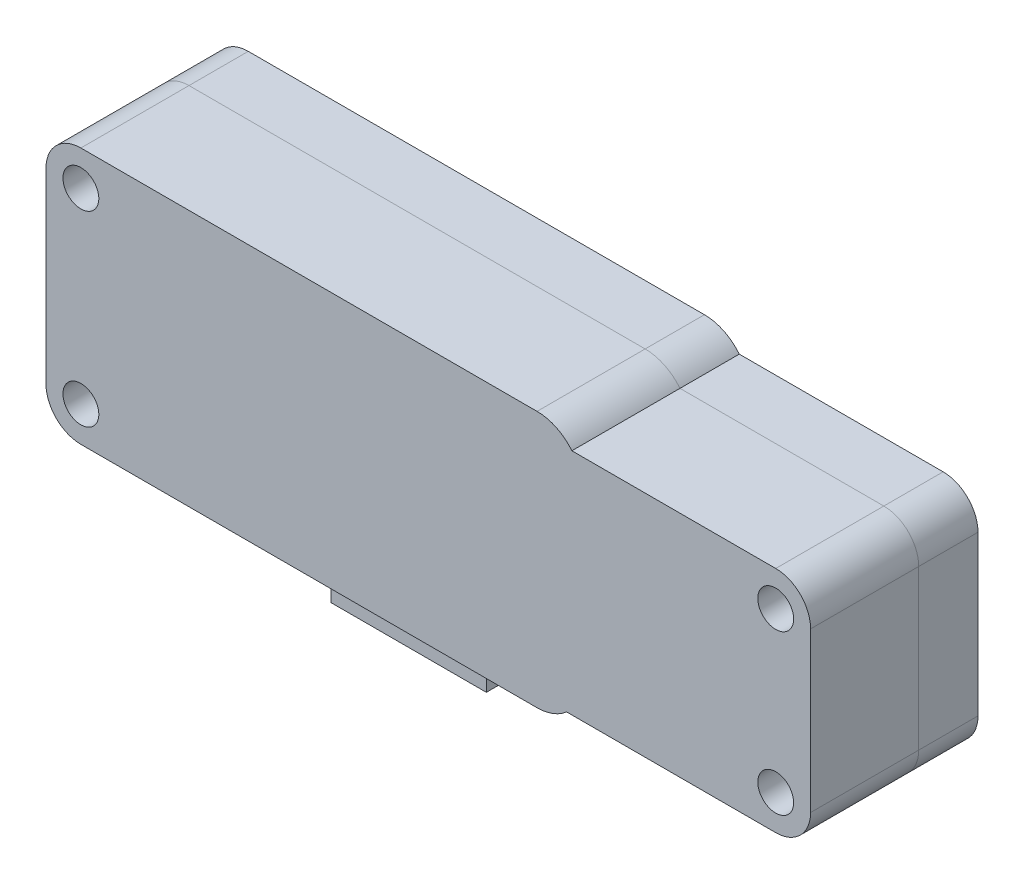
SolidWorks part; units mm, degrees
ref_plane "Front Plane" through (0, 0, 0) normal (0, 0, 1) x (1, 0, 0)
ref_plane "Top Plane" through (0, 0, 0) normal (0, 1, 0) x (1, 0, 0)
ref_plane "Right Plane" through (0, 0, 0) normal (1, 0, 0) x (0, 0, -1)
sketch "Sketch1" plane through (0, 0, 2.064) normal (0, 0, 1) x (1, 0, 0)
  line L8 (-21.844, 7.62) -> (-21.844, -7.62)
  line L9 (17.78, 11.684) -> (-17.78, 11.684)
  line L10 (21.844, -7.62) -> (21.844, 7.62)
  line L11 (-17.78, -11.684) -> (17.78, -11.684)
  line L12 (-21.844, 7.62) -> (-21.844, -7.62)
  line L13 (17.78, 11.684) -> (-17.78, 11.684)
  line L14 (21.844, -7.62) -> (21.844, 7.62)
  line L15 (-17.78, -11.684) -> (17.78, -11.684)
  arc A8 (-17.78, 11.684) -> (-21.844, 7.62) centre (-17.78, 7.62) ccw
  arc A9 (21.844, 7.62) -> (17.78, 11.684) centre (17.78, 7.62) ccw
  arc A10 (17.78, -11.684) -> (21.844, -7.62) centre (17.78, -7.62) ccw
  arc A11 (-21.844, -7.62) -> (-17.78, -11.684) centre (-17.78, -7.62) ccw
  arc A12 (-17.78, 11.684) -> (-21.844, 7.62) centre (-17.78, 7.62) ccw
  arc A13 (21.844, 7.62) -> (17.78, 11.684) centre (17.78, 7.62) ccw
  arc A14 (17.78, -11.684) -> (21.844, -7.62) centre (17.78, -7.62) ccw
  arc A15 (-21.844, -7.62) -> (-17.78, -11.684) centre (-17.78, -7.62) ccw
  dimension "D1" = 1.524
extrude "Boss-Extrude1" add sketch "Sketch1" against normal blind 12.7 from offset 0.508
ref_plane "Plane2" through (0, 0, -4) normal (0, 0, -1) x (-1, 0, 0)
sketch "Sketch2" plane through (0, 0, -4) normal (0, 0, -1) x (-1, 0, 0)
  line L3 (4.276, -16.0786) -> (4.276, -8.1284)
  line L4 (3.006, -14.8086) -> (-8.594, -14.8086) construction
  line L5 (3.006, -14.8086) -> (3.006, -9.3984) construction
  line L6 (3.006, -9.3984) -> (-8.594, -9.3984) construction
  line L7 (-8.594, -14.8086) -> (-8.594, -9.3984) construction
  line L8 (4.276, -8.1284) -> (-9.864, -8.1284)
  line L9 (-9.864, -16.0786) -> (-9.864, -8.1284)
  line L10 (4.276, -16.0786) -> (-9.864, -16.0786)
  line L12 (3.006, -14.8086) -> (3.006, -9.3984) construction
  line L13 (-8.594, -14.8086) -> (-3.048, -14.8086) construction
  dimension "D1" = 1.27
extrude "Boss-Extrude2" add sketch "Sketch2" along normal offset from surface 1.27 and the other way offset from surface (3.27 mm away) 1.27
sketch "Sketch3" plane through (0, 0, -10.128) normal (0, 0, -1) x (-1, 0, 0)
  line L1 (-2.794, 8.8916) -> (-36.334, 8.8916) construction
  line L2 (-2.794, 8.8916) -> (-2.794, -9.3984) construction
  line L3 (-2.794, -9.3984) -> (-36.334, -9.3984) construction
  line L4 (-36.334, 8.8916) -> (-36.334, -9.3984) construction
  line L5 (-36.334, 8.8916) -> (-36.334, -9.3984) construction
  line L6 (-36.334, -9.3984) -> (-2.794, -9.3984) construction
  line L7 (-1.524, 10.1616) -> (-37.604, 10.1616)
  line L8 (-37.604, 10.1616) -> (-37.604, -10.6684)
  line L9 (-1.524, -10.6684) -> (-37.604, -10.6684)
  line L10 (-1.524, 10.1616) -> (-1.524, -10.6684)
  dimension "D1" = 1.27
extrude "Boss-Extrude3" add sketch "Sketch3" along normal blind 2.54 and the other way up to surface contours L9 L8 L7 L10 other way up to face at (0, 0, 2.572)
sketch "Sketch7" plane through (0, -16.0786, 0) normal (0, -1, 0) x (1, 0, 0)
  line L0 (-0.218, -5.762) -> (-0.218, -2.238)
  line L1 (0.544, -5) -> (5.044, -5) construction
  line L2 (0.544, -5) -> (0.544, -3) construction
  line L3 (0.544, -3) -> (5.044, -3) construction
  line L4 (5.044, -5) -> (5.044, -3) construction
  line L5 (-0.218, -2.238) -> (5.806, -2.238)
  line L6 (5.806, -5.762) -> (5.806, -2.238)
  line L7 (-0.218, -5.762) -> (5.806, -5.762)
  dimension "D1" = 0.762
extrude "Cut-Extrude1" cut sketch "Sketch7" against normal blind 2.54
sketch "Sketch11" plane through (0, 0, -10.128) normal (0, 0, -1) x (-1, 0, 0)
  line L4 (17.78, 11.684) -> (23.749, 11.684)
  line L5 (26.924, 7.62) -> (26.924, -7.62)
  line L6 (26.924, 8.509) -> (26.924, -8.509)
  line L7 (17.78, -11.684) -> (23.749, -11.684)
  line L8 (-20.9512, 10.1616) -> (-1.524, 10.1616)
  line L9 (-20.9512, 10.1616) -> (-1.524, 10.1616)
  line L12 (-1.524, 10.1616) -> (-1.524, -10.6684)
  line L13 (-1.524, 10.1616) -> (-1.524, -10.6684)
  line L14 (-1.524, -10.6684) -> (-20.4677, -10.6684)
  line L15 (-1.524, -10.6684) -> (-20.4677, -10.6684)
  line L17 (-17.78, -11.684) -> (17.78, -11.684)
  line L18 (21.844, -7.62) -> (21.844, 7.62)
  line L19 (17.78, 11.684) -> (-17.78, 11.684)
  line L23 (-17.78, -11.684) -> (17.78, -11.684)
  line L25 (17.78, 11.684) -> (-17.78, 11.684)
  arc A2 (23.749, -11.684) -> (26.924, -8.509) centre (23.749, -8.509) ccw
  arc A3 (26.924, 8.509) -> (23.749, 11.684) centre (23.749, 8.509) ccw
  arc A8 (-17.78, 11.684) -> (-20.9512, 10.1616) centre (-17.78, 7.62) ccw
  arc A9 (-20.4677, -10.6684) -> (-17.78, -11.684) centre (-17.78, -7.62) ccw
  arc A10 (17.78, -11.684) -> (21.844, -7.62) centre (17.78, -7.62) ccw
  arc A11 (21.844, 7.62) -> (17.78, 11.684) centre (17.78, 7.62) ccw
  arc A12 (-17.78, 11.684) -> (-20.9512, 10.1616) centre (-17.78, 7.62) ccw
  arc A13 (-20.4677, -10.6684) -> (-17.78, -11.684) centre (-17.78, -7.62) ccw
  dimension "D2" = 3.175
  dimension "D1" = 5.08
  dimension "D3" = 0
extrude "Boss-Extrude5" add sketch "Sketch11" against normal through all
hole_wizard "#4 Clearance Hole4" positions "Sketch13" profile "Sketch12" hole size "#4" standard "ANSI Inch" end condition through all
sketch "Sketch13" plane through (0, 0, -10.128) normal (0, 0, -1) x (-1, 0, 0)
  line L0 (26.924, 0) -> (-37.604, -0.2534) construction
  line L1 (26.924, -8.509) -> (26.924, 8.509) construction
  line L2 (-37.604, 10.1616) -> (-37.604, -10.6684) construction
  point P9 (23.749, 8.509)
  point P12 (23.749, -8.509)
sketch "Sketch12" plane through (-23.749, 8.509, -10.128) normal (1, 0, 0) x (0, 1, 0)
  line L0 (0, 0) -> (0, 12.7)
  line L1 (0, 12.7) -> (1.6319, 12.7)
  line L2 (1.6319, 12.7) -> (1.6319, 0)
  line L5 (1.6319, 0) -> (0, 0)
  line L11 (0, -6.35) -> (0, 107.95) construction
  dimension "Thru Hole Dia." = 3.2639
  dimension "Thru Hole Depth" = 12.7
sketch "Sketch14" plane through (0, 0, -12.668) normal (0, 0, -1) x (-1, 0, 0)
  line L0 (-37.604, 10.1616) -> (-39.509, 10.1616)
  line L1 (-42.684, 6.9866) -> (-42.684, -7.4934)
  line L2 (-39.509, -10.6684) -> (-37.604, -10.6684)
  line L7 (-1.524, -10.6684) -> (-1.524, 10.1616)
  line L8 (-1.524, 10.1616) -> (-37.604, 10.1616)
  line L9 (-37.604, 10.1616) -> (-37.604, -10.6684)
  line L10 (-37.604, -10.6684) -> (-1.524, -10.6684)
  line L13 (-37.604, 10.1616) -> (-37.604, -10.6684)
  arc A0 (-42.684, -7.4934) -> (-39.509, -10.6684) centre (-39.509, -7.4934) ccw
  arc A1 (-42.684, 6.9866) -> (-39.509, 10.1616) centre (-39.509, 6.9866) cw
  point P10 (-42.684, 10.1616)
  dimension "D2" = 3.175
  dimension "D1" = 5.08
  dimension "D3" = 0
extrude "Boss-Extrude6" add sketch "Sketch14" against normal through all
hole_wizard "#4 Clearance Hole5" positions "Sketch16" profile "Sketch15" hole size "#4" standard "ANSI Inch" end condition through all
sketch "Sketch16" plane through (0, 0, -12.668) normal (0, 0, -1) x (-1, 0, 0)
  line L0 (-42.684, -0.2534) -> (-1.524, -0.2534) construction
  line L1 (-42.684, 6.9866) -> (-42.684, -7.4934) construction
  line L2 (-1.524, 10.1616) -> (-1.524, -10.6684) construction
  point P9 (-39.509, 6.9866)
  point P12 (-39.509, -7.4934)
sketch "Sketch15" plane through (39.509, 6.9866, -12.668) normal (1, 0, 0) x (0, 1, 0)
  line L0 (0, 0) -> (0, 15.24)
  line L1 (0, 15.24) -> (1.6319, 15.24)
  line L2 (1.6319, 15.24) -> (1.6319, 0)
  line L5 (1.6319, 0) -> (0, 0)
  line L11 (0, -6.35) -> (0, 107.95) construction
  dimension "Thru Hole Dia." = 3.2639
  dimension "Thru Hole Depth" = 15.24
sketch "Sketch17" plane through (0, 0, -10.128) normal (0, 0, -1) x (-1, 0, 0)
  line L12 (-17.78, -11.684) -> (23.749, -11.684)
  line L13 (26.924, -8.509) -> (26.924, 8.509)
  line L14 (23.749, 11.684) -> (-17.78, 11.684)
  line L15 (-20.9512, 10.1616) -> (-1.524, 10.1616)
  line L16 (-1.524, 10.1616) -> (-1.524, -10.6684)
  line L17 (-1.524, -10.6684) -> (-20.4677, -10.6684)
  line L18 (-17.78, -11.684) -> (23.749, -11.684)
  line L19 (26.924, -8.509) -> (26.924, 8.509)
  line L20 (23.749, 11.684) -> (-17.78, 11.684)
  line L21 (-20.9512, 10.1616) -> (-1.524, 10.1616)
  line L22 (-1.524, 10.1616) -> (-1.524, -10.6684)
  line L23 (-1.524, -10.6684) -> (-20.4677, -10.6684)
  circle A4 centre (23.749, 8.509) radius 1.6319
  circle A5 centre (23.749, -8.509) radius 1.6319
  arc A8 (23.749, -11.684) -> (26.924, -8.509) centre (23.749, -8.509) ccw
  arc A9 (26.924, 8.509) -> (23.749, 11.684) centre (23.749, 8.509) ccw
  arc A10 (-17.78, 11.684) -> (-20.9512, 10.1616) centre (-17.78, 7.62) ccw
  arc A11 (-20.4677, -10.6684) -> (-17.78, -11.684) centre (-17.78, -7.62) ccw
  arc A12 (23.749, -11.684) -> (26.924, -8.509) centre (23.749, -8.509) ccw
  arc A13 (26.924, 8.509) -> (23.749, 11.684) centre (23.749, 8.509) ccw
  arc A14 (-17.78, 11.684) -> (-20.9512, 10.1616) centre (-17.78, 7.62) ccw
  arc A15 (-20.4677, -10.6684) -> (-17.78, -11.684) centre (-17.78, -7.62) ccw
  dimension "D1" = 0
extrude "Boss-Extrude8" add sketch "Sketch17" along normal up to surface (2.54 mm away) up to face at (37.877, 6.9866, -12.668)
ref_plane "Plane1" through (0, 0, -7.27) normal (0, 0, -1) x (-1, 0, 0)
split "Split1" trim tools "Plane1" bodies to split 109 resulting bodies 107 108
